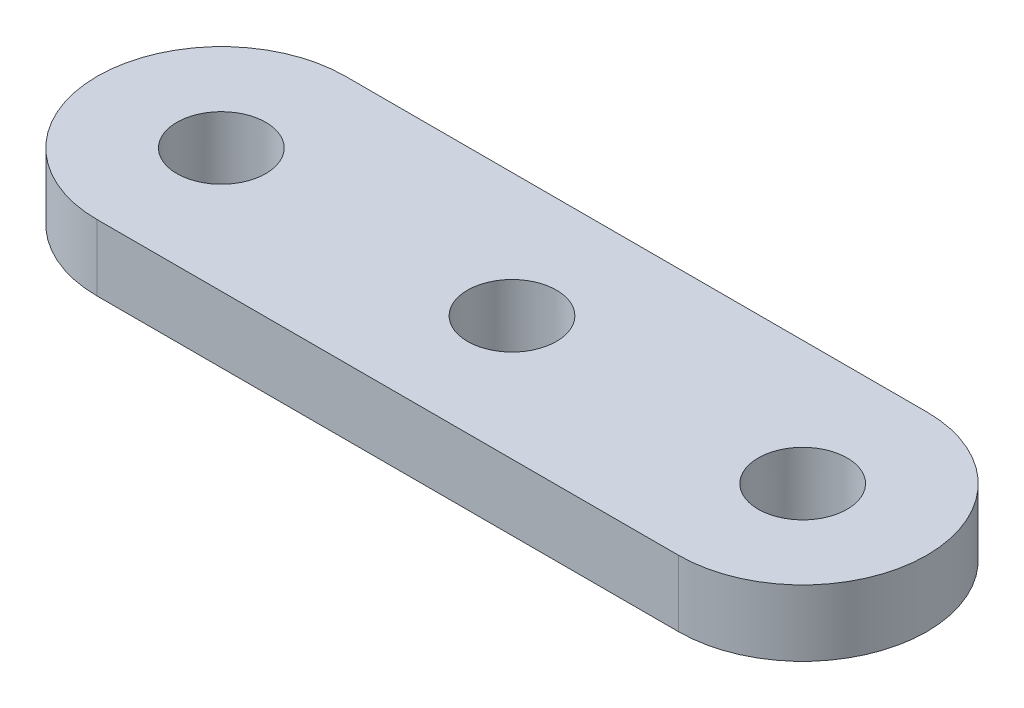
SolidWorks part; units mm, degrees
ref_plane "Front Plane" through (0, 0, 0) normal (0, 0, 1) x (1, 0, 0)
ref_plane "Top Plane" through (0, 0, 0) normal (0, 1, 0) x (1, 0, 0)
ref_plane "Right Plane" through (0, 0, 0) normal (1, 0, 0) x (0, 0, -1)
sketch "Sketch3" plane through (0, 0, 0) normal (0, 1, 0) x (1, 0, 0)
  line L1 (-14.05, 6) -> (14.05, 6)
  line L3 (-14.05, -6) -> (14.05, -6)
  arc A0 (-14.05, 6) -> (-14.05, -6) centre (-14.05, 0) ccw
  arc A1 (14.05, 6) -> (14.05, -6) centre (14.05, 0) cw
  point P0 (0, 0)
  dimension "D3" = 6
  dimension "D4" = 6
  dimension "D1" = 28.1
  dimension "D2" = 14.05
  dimension "D5" = 14.05
extrude "Boss-Extrude2" add sketch "Sketch3" along normal blind 3.2
sketch "Sketch11" plane through (0, 3.2, 0) normal (0, 1, 0) x (1, 0, 0)
  point P0 (0, 0)
  point P3 (14.05, 0)
  point P6 (-14.05, 0)
hole_wizard "M4 Clearance Hole4" positions "Sketch11" profile "Sketch12" hole size "M4" standard "ANSI Metric" end condition up to next
sketch "Sketch12" plane through (0, 3.2, 0) normal (1, 0, 0) x (0, 0, 1)
  line L0 (0, 0) -> (0, 3.2)
  line L1 (0, 3.2) -> (2.15, 3.2)
  line L2 (2.15, 3.2) -> (2.15, 0)
  line L5 (2.15, 0) -> (0, 0)
  line L11 (0, -6.35) -> (0, 107.95) construction
  dimension "Thru Hole Dia." = 4.3
  dimension "Thru Hole Depth" = 3.2
